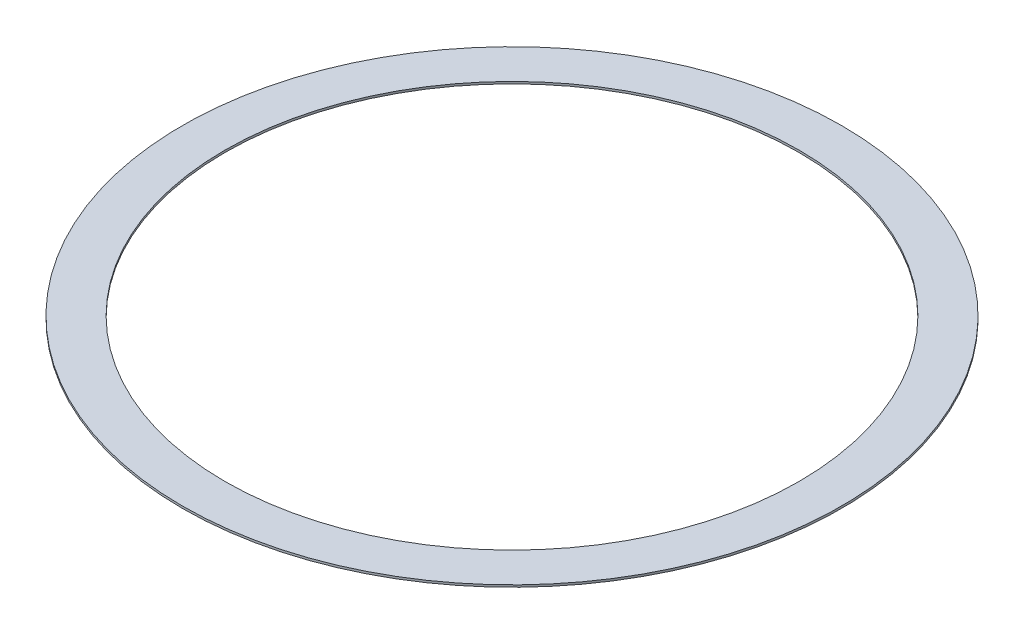
SolidWorks part; units mm, degrees
ref_plane "Front Plane" through (0, 0, 0) normal (0, 0, 1) x (1, 0, 0)
ref_plane "Top Plane" through (0, 0, 0) normal (0, 1, 0) x (1, 0, 0)
ref_plane "Right Plane" through (0, 0, 0) normal (1, 0, 0) x (0, 0, -1)
sketch "Sketch1" plane through (0, 0, 0) normal (0, 1, 0) x (1, 0, 0)
  circle A0 centre (0, 0) radius 15.5
  circle A1 centre (0, 0) radius 13.5
  dimension "D1" = 31
  dimension "D2" = 27
extrude "Boss-Extrude1" add sketch "Sketch1" along normal blind 0.1
